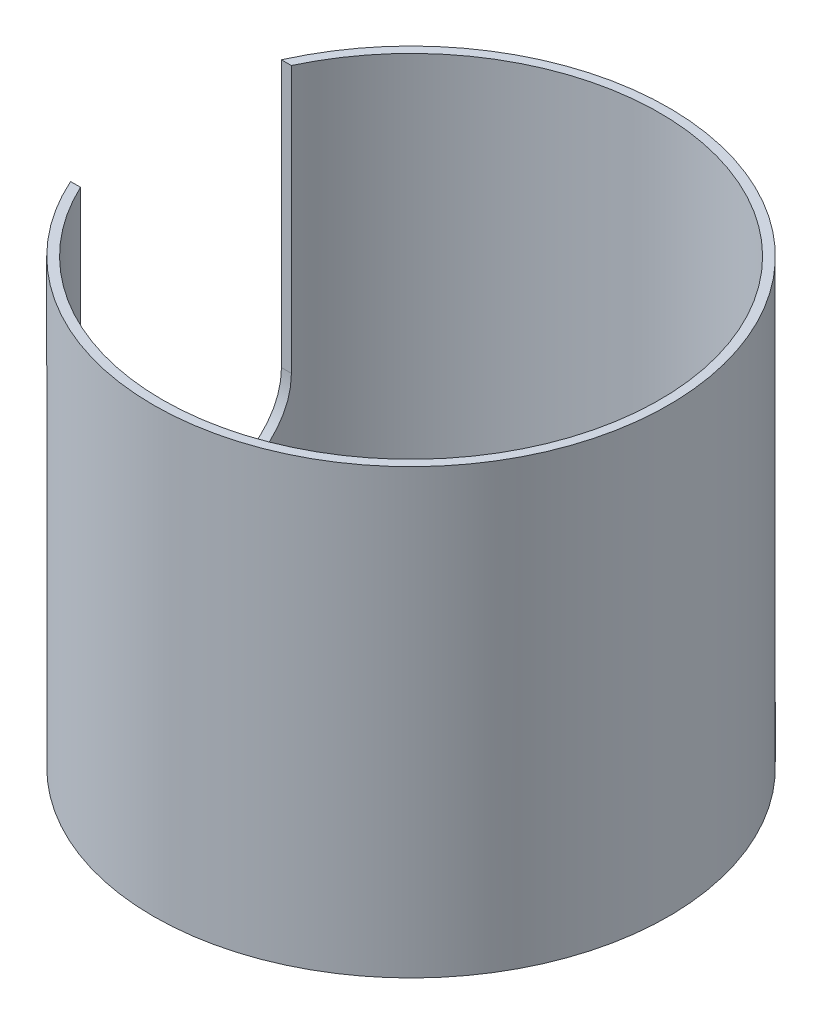
SolidWorks part; units mm, degrees
material "6061 Alloy"
ref_plane "Front Plane" through (0, 0, 0) normal (0, 0, 1) x (1, 0, 0)
ref_plane "Top Plane" through (0, 0, 0) normal (0, 1, 0) x (1, 0, 0)
ref_plane "Right Plane" through (0, 0, 0) normal (1, 0, 0) x (0, 0, -1)
sketch "Sketch1" plane through (0, 0, 0) normal (0, 1, 0) x (1, 0, 0)
  circle A0 centre (0, 0) radius 27.506
  circle A1 centre (0, 0) radius 28.506
  dimension "D2" = 55.012
  dimension "D1" = 1
extrude "Boss-Extrude1" add sketch "Sketch1" along normal blind 48 and the other way blind 1
sketch "Sketch2" plane through (0, 0, 0) normal (1, 0, 0) x (0, 0, -1)
  line L0 (-28.506, -1) -> (28.506, -1) construction
  line L1 (11.666, 18.5) -> (11.666, 48)
  line L2 (27.506, 48) -> (-27.506, 48) construction
  line L3 (-11.666, 18.5) -> (-11.666, 48)
  line L4 (-11.666, 48) -> (11.666, 48)
  arc A0 (-11.666, 18.5) -> (11.666, 18.5) centre (0, 18.5) ccw
  dimension "D2" = 23.332
  dimension "D1" = 19.5
extrude "Cut-Extrude1" cut sketch "Sketch2" against normal blind 48
